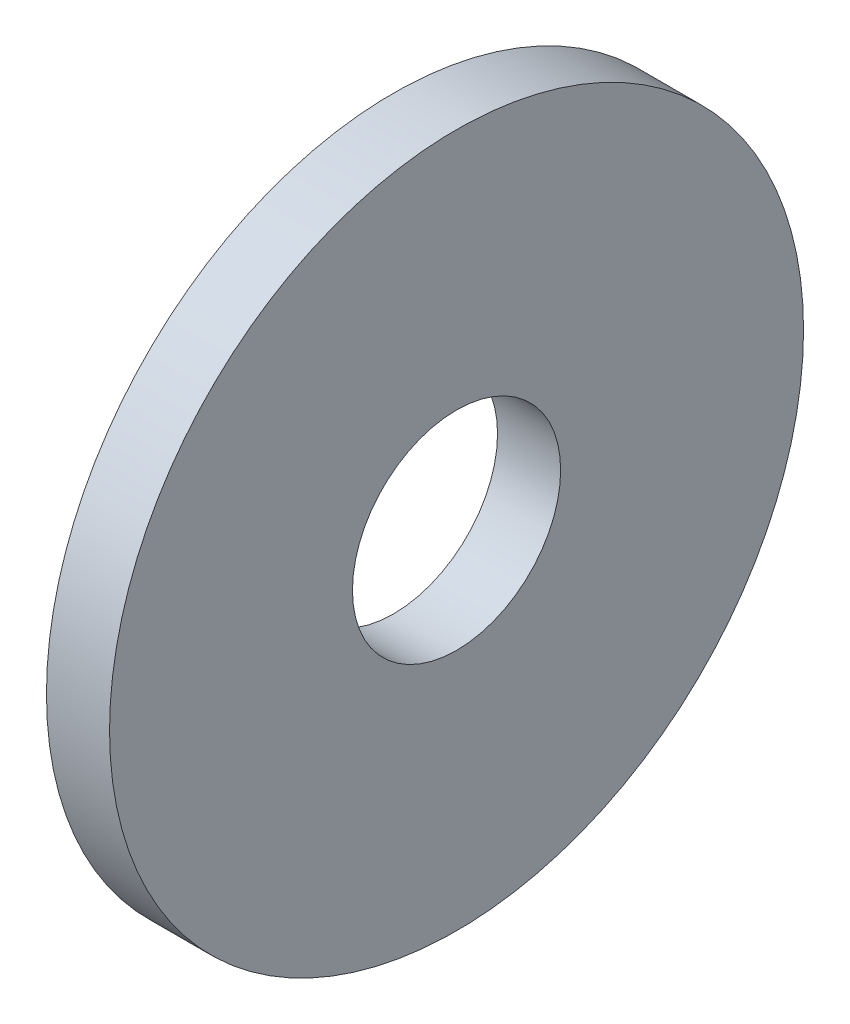
SolidWorks part; units mm, degrees
ref_plane "Plane1" through (0, 0, 0) normal (0, 0, 1) x (1, 0, 0)
ref_plane "Plane2" through (0, 0, 0) normal (0, 1, 0) x (1, 0, 0)
ref_plane "Plane3" through (0, 0, 0) normal (1, 0, 0) x (0, 0, -1)
sketch "Sketch1" plane through (0, 0, 0) normal (0, 0, 1) x (1, 0, 0)
  line L0 (-34.925, 0) -> (9.525, 0) construction
  line L1 (0, 3.3) -> (0, 11)
  line L2 (0, 11) -> (-2, 11)
  line L3 (-2, 11) -> (-2, 3.3)
  line L4 (-2, 3.3) -> (0, 3.3)
  dimension "Thickness" = 2
  dimension "Inside_dia" = 6.6
  dimension "Outside_dia" = 22
revolve "Base-Revolve" add sketch "Sketch1" angle 360 about L0
